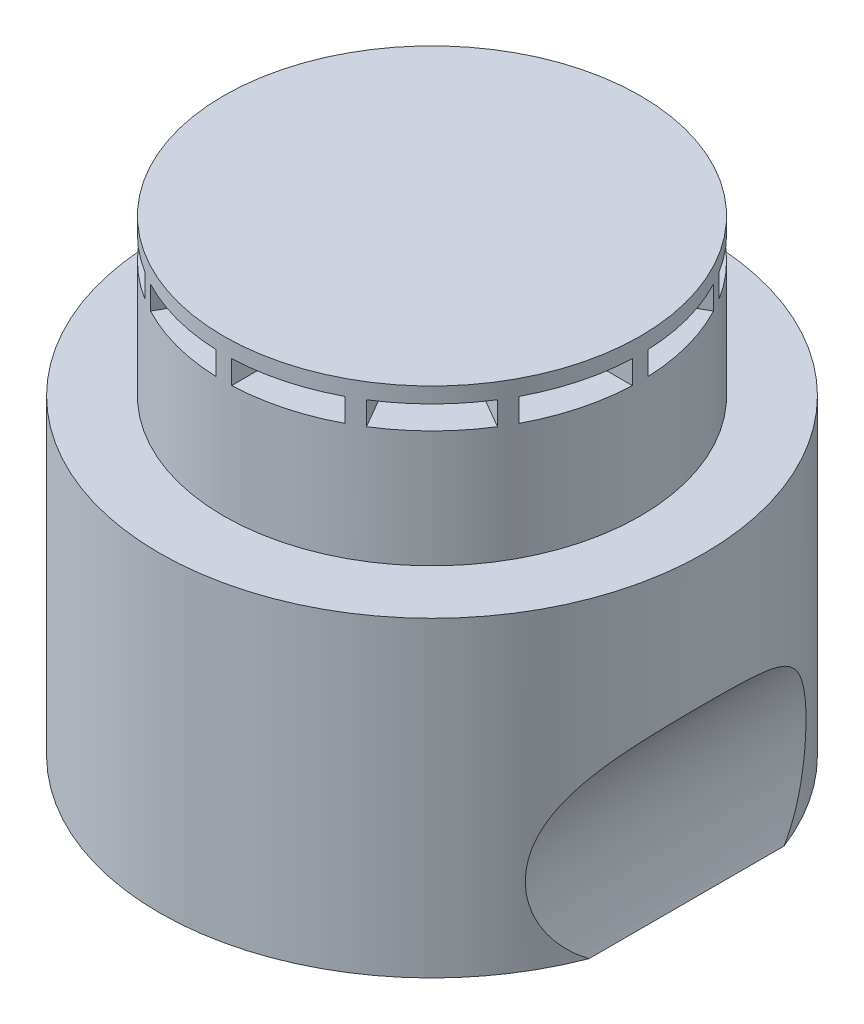
SolidWorks part; units mm, degrees
ref_plane "前视基准面" through (0, 0, 0) normal (0, 0, 1) x (1, 0, 0)
ref_plane "上视基准面" through (0, 0, 0) normal (0, 1, 0) x (1, 0, 0)
ref_plane "右视基准面" through (0, 0, 0) normal (1, 0, 0) x (0, 0, -1)
sketch "草图1" plane through (0, 0, 0) normal (0, 1, 0) x (1, 0, 0)
  circle A0 centre (0, 0) radius 70
  dimension "D1" = 140
extrude "凸台-拉伸1" add sketch "草图1" along normal blind 80
sketch "草图2" plane through (0, 80, 0) normal (0, 1, 0) x (1, 0, 0)
  circle A0 centre (0, 0) radius 53.5
  dimension "D1" = 107
extrude "凸台-拉伸2" add sketch "草图2" along normal blind 40
ref_plane "基准面1" through (0, 110, 0) normal (0, 1, 0) x (1, 0, 0)
sketch "草图3" plane through (0, 110, 0) normal (0, 1, 0) x (1, 0, 0)
  line L0 (0, 0) -> (0, 53.5) construction
  line L1 (2, 39.95) -> (2, 53.4626)
  line L2 (-2, 39.95) -> (-2, 53.4626)
  line L3 (21.707, 33.5977) -> (28.4634, 45.3)
  line L4 (18.2429, 35.5977) -> (24.9993, 47.3)
  line L5 (0, 0) -> (26.75, 46.3324) construction
  line L6 (35.5977, 18.2429) -> (47.3, 24.9993)
  line L7 (33.5977, 21.707) -> (45.3, 28.4634)
  line L8 (0, 0) -> (46.3324, 26.75) construction
  line L9 (39.95, -2) -> (53.4626, -2)
  line L10 (39.95, 2) -> (53.4626, 2)
  line L11 (0, 0) -> (53.5, 0) construction
  line L12 (33.5977, -21.707) -> (45.3, -28.4634)
  line L13 (35.5977, -18.2429) -> (47.3, -24.9993)
  line L14 (0, 0) -> (46.3324, -26.75) construction
  line L15 (18.2429, -35.5977) -> (24.9993, -47.3)
  line L16 (21.707, -33.5977) -> (28.4634, -45.3)
  line L17 (0, 0) -> (26.75, -46.3324) construction
  line L18 (-2, -39.95) -> (-2, -53.4626)
  line L19 (2, -39.95) -> (2, -53.4626)
  line L20 (0, 0) -> (0, -53.5) construction
  line L21 (-21.707, -33.5977) -> (-28.4634, -45.3)
  line L22 (-18.2429, -35.5977) -> (-24.9993, -47.3)
  line L23 (0, 0) -> (-26.75, -46.3324) construction
  line L24 (-35.5977, -18.2429) -> (-47.3, -24.9993)
  line L25 (-33.5977, -21.707) -> (-45.3, -28.4634)
  line L26 (0, 0) -> (-46.3324, -26.75) construction
  line L27 (-39.95, 2) -> (-53.4626, 2)
  line L28 (-39.95, -2) -> (-53.4626, -2)
  line L29 (0, 0) -> (-53.5, 0) construction
  line L30 (-33.5977, 21.707) -> (-45.3, 28.4634)
  line L31 (-35.5977, 18.2429) -> (-47.3, 24.9993)
  line L32 (0, 0) -> (-46.3324, 26.75) construction
  line L33 (-18.2429, 35.5977) -> (-24.9993, 47.3)
  line L34 (-21.707, 33.5977) -> (-28.4634, 45.3)
  line L35 (0, 0) -> (-26.75, 46.3324) construction
  circle A0 centre (0, 0) radius 40
  circle A1 centre (0, 0) radius 40
  circle A2 centre (0, 0) radius 53.5
  circle A3 centre (0, 0) radius 53.5
  circle A4 centre (0, 0) radius 40
  circle A5 centre (0, 0) radius 40
  circle A6 centre (0, 0) radius 40
  circle A7 centre (0, 0) radius 40
  circle A8 centre (0, 0) radius 40
  circle A9 centre (0, 0) radius 40
  circle A10 centre (0, 0) radius 40
  circle A11 centre (0, 0) radius 40
  circle A12 centre (0, 0) radius 40
  circle A13 centre (0, 0) radius 40
  dimension "D1" = 80
  dimension "D3" = 2
  dimension "D2" = 0
  dimension "D4" = 12
extrude "切除-拉伸1" cut sketch "草图3" along normal blind 6 contours L28 A3 L24 A0 | L31 A3 L27 A0 | L34 A3 L30 A0 | L2 A3 L33 A0 | L4 A3 L1 A0 | L7 A3 L3 A0 | L10 A3 L6 A0 | L13 A3 L9 A0 | L16 A3 L12 A0 | L19 A3 L15 A0 | L22 A3 L18 A0 | L25 A3 L21 A0
sketch "草图4" plane through (0, 0, 0) normal (0, 0, 1) x (1, 0, 0)
  line L0 (0, 0) -> (100, 0) construction
  line L1 (100, 0) -> (100, 20)
  circle A0 centre (100, 20) radius 40
  dimension "D2" = 80
  dimension "D1" = 20
  dimension "D3" = 100
extrude "切除-拉伸2" cut sketch "草图4" against normal through all both and the other way through all
mirror "镜向1" about plane through (0, 0, 0) normal (1, 0, 0) of "切除-拉伸2"
sketch "草图5" plane through (0, 0, 0) normal (0, 0, 1) x (1, 0, 0)
  line L0 (-65.359, 0) -> (65.359, 0) construction
  line L1 (-42, -60) -> (42, -60)
  line L2 (-42, -60) -> (-42, 60)
  line L3 (-42, 60) -> (42, 60)
  line L4 (42, -60) -> (42, 60)
  line L5 (-42, -60) -> (42, 60) construction
  line L6 (-42, 60) -> (42, -60) construction
  point P0 (0, 0)
  dimension "D1" = 60
  dimension "D2" = 84
extrude "切除-拉伸3" cut sketch "草图5" against normal through all and the other way blind 30
sketch "草图6" plane through (0, 0, 0) normal (0, -1, 0) x (1, 0, 0)
  line L0 (0, 30) -> (0, -70) construction
  line L1 (42, 30) -> (-42, 30) construction
  arc A0 (-42, -56) -> (42, -56) centre (0, 0) ccw construction
